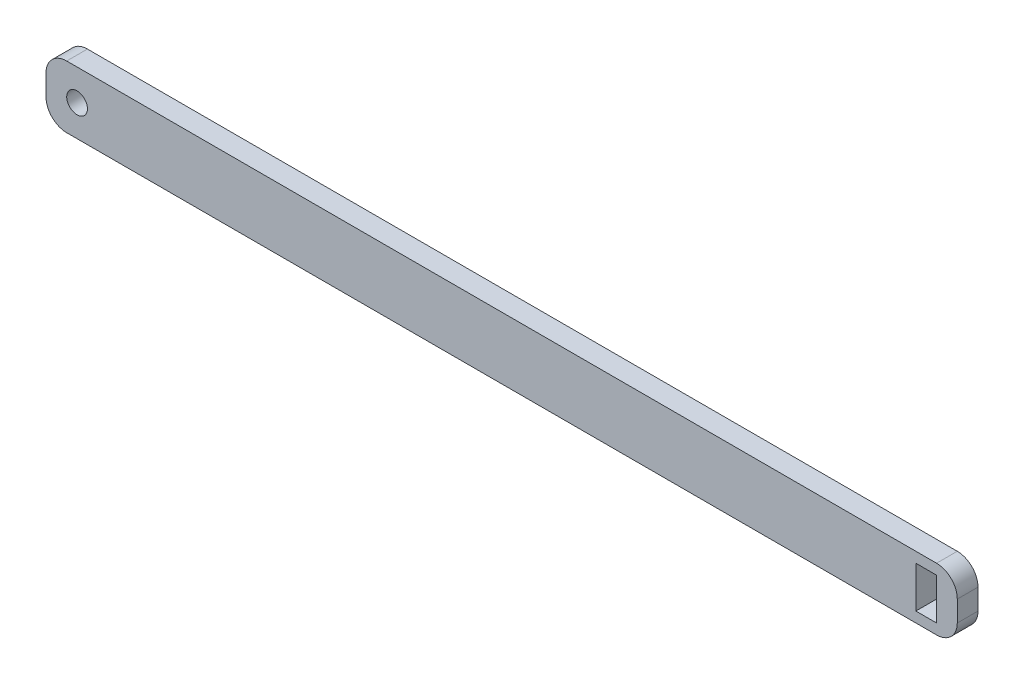
SolidWorks part; units mm, degrees
ref_plane "Front Plane" through (0, 0, 0) normal (0, 0, 1) x (1, 0, 0)
ref_plane "Top Plane" through (0, 0, 0) normal (0, 1, 0) x (1, 0, 0)
ref_plane "Right Plane" through (0, 0, 0) normal (1, 0, 0) x (0, 0, -1)
sketch "Sketch1" plane through (0, 0, 0) normal (0, 0, 1) x (1, 0, 0)
  line L5 (-215, 15) -> (-5, 15)
  line L6 (-220, 10) -> (-220, 5)
  line L7 (-215, 0) -> (-5, 0)
  line L8 (0, 10) -> (0, 5)
  line L9 (-10, 12.5) -> (-5, 12.5)
  line L10 (-10, 12.5) -> (-10, 2.5)
  line L11 (-10, 2.5) -> (-5, 2.5)
  line L12 (-5, 12.5) -> (-5, 2.5)
  arc A0 (-220, 5) -> (-215, 0) centre (-215, 5) ccw
  arc A1 (-215, 15) -> (-220, 10) centre (-215, 10) ccw
  arc A2 (-5, 0) -> (0, 5) centre (-5, 5) ccw
  arc A3 (-5, 15) -> (0, 10) centre (-5, 10) cw
  circle A4 centre (-212.5, 7.5) radius 2.5
  point P3 (-220, 0)
  point P11 (-220, 15)
  dimension "D3" = 5
  dimension "D4" = 5
  dimension "D6" = 7.5
  dimension "D7" = 5
  dimension "D8" = 2.5
  dimension "D9" = 5
  dimension "D1" = 10
  dimension "D2" = 15
  dimension "D5" = 7.5
extrude "Boss-Extrude1" add sketch "Sketch1" along normal blind 5
